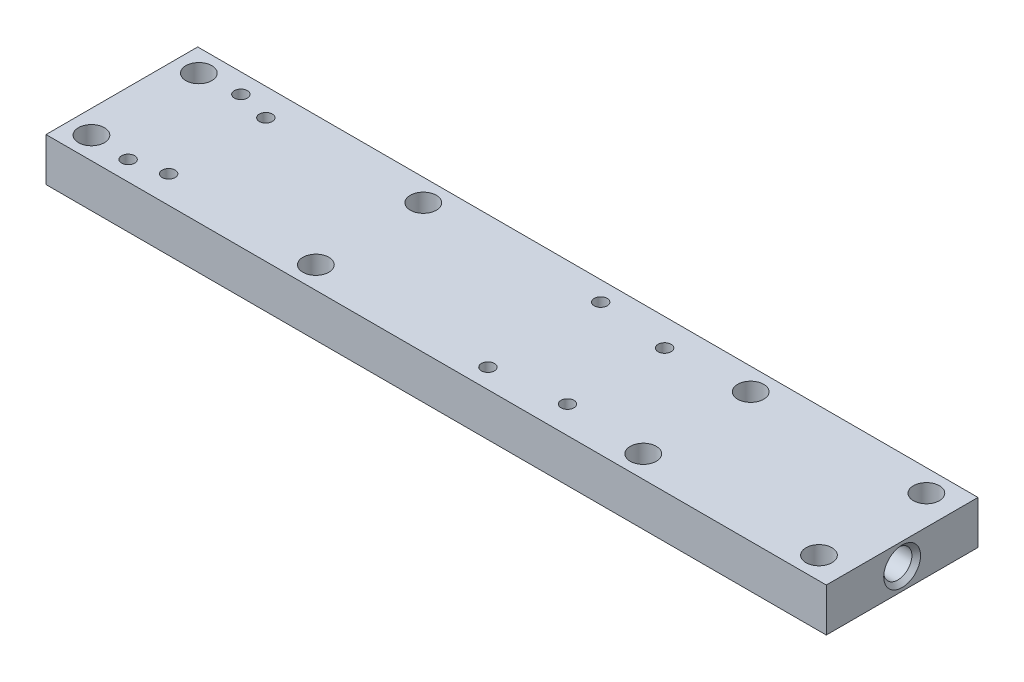
SolidWorks part; units mm, degrees
ref_plane "Front Plane" through (0, 0, 0) normal (0, 0, 1) x (1, 0, 0)
ref_plane "Top Plane" through (0, 0, 0) normal (0, 1, 0) x (1, 0, 0)
ref_plane "Right Plane" through (0, 0, 0) normal (1, 0, 0) x (0, 0, -1)
sketch "Sketch1" plane through (0, 0, 0) normal (0, 1, 0) x (1, 0, 0)
  line L0 (0, -55) -> (0, 55) construction
  line L1 (-90, 17.5) -> (90, 17.5)
  line L2 (-90, 17.5) -> (-90, -17.5)
  line L3 (-90, -17.5) -> (90, -17.5)
  line L4 (90, 17.5) -> (90, -17.5)
  line L5 (-5.5, 0) -> (5.5, 0) construction
  point P4 (0, 17.5)
  point P7 (-90, 0)
  dimension "D1" = 180
  dimension "D2" = 35
extrude "Boss-Extrude1" add sketch "Sketch1" along normal mid plane 10
sketch "Sketch3" plane through (90, 0, 0) normal (1, 0, 0) x (0, 0, -1)
  circle A0 centre (0, 0) radius 3.25
  dimension "D1" = 6.5
extrude "Cut-Extrude1" cut sketch "Sketch3" against normal through all
chamfer "Chamfer1" distance 1 angle 45 1 edges at (90, 0, -3.25)
chamfer "Chamfer2" distance 1 angle 45 1 edges at (-90, 0, -3.25)
sketch "Sketch4" plane through (0, 0, 0) normal (0, 0, 1) x (1, 0, 0)
sketch "Sketch5" plane through (0, 5, 0) normal (0, 1, 0) x (1, 0, 0)
  line L6 (-68, 11.2) -> (-68, -11.2) construction
  line L7 (-5.5, 0) -> (5.5, 0) construction
  line L8 (24, 11.2) -> (24, -11.2) construction
  line L9 (-90, 17.5) -> (-90, -17.5) construction
  circle A0 centre (-68, -11.2) radius 1.5
  circle A1 centre (-68, 11.2) radius 1.5
  circle A2 centre (24, 11.2) radius 1.5
  circle A3 centre (24, -11.2) radius 1.5
  point P4 (-68, 0)
  point P7 (24, 0)
  dimension "D4" = 3
  dimension "D5" = 3
  dimension "D6" = 3
  dimension "D7" = 3
  dimension "D1" = 92
  dimension "D2" = 22.4
  dimension "D3" = 22.4
  dimension "D8" = 22
extrude "Cut-Extrude2" cut sketch "Sketch5" against normal blind 10
sketch "Sketch18" plane through (0, 5, 0) normal (0, 1, 0) x (1, 0, 0)
  line L0 (-75.5526, 13) -> (-75.5526, -13) construction
  line L1 (-75.5526, -13) -> (7.4474, -13) construction
  line L2 (7.4474, -13) -> (7.4474, 13) construction
  line L3 (7.4474, 13) -> (-75.5526, 13) construction
  line L4 (-5.5, 0) -> (5.5, 0) construction
  circle A0 centre (-75.5526, 13) radius 1.5
  circle A1 centre (-75.5526, -13) radius 1.5
  circle A2 centre (7.4474, -13) radius 1.5
  circle A3 centre (7.4474, 13) radius 1.5
  point P2 (-75.5526, 0)
  dimension "D3" = 3
  dimension "D4" = 3
  dimension "D5" = 3
  dimension "D6" = 3
  dimension "D1" = 83
  dimension "D2" = 26
extrude "Cut-Extrude3" cut sketch "Sketch18" against normal blind 36
sketch "Sketch19" plane through (0, 5, 0) normal (0, 1, 0) x (1, 0, 0)
  line L0 (-84.6324, 12.3902) -> (-84.6324, -12.3902) construction
  line L1 (-84.6324, -12.3902) -> (83.204, -12.3902) construction
  line L2 (83.204, -12.3902) -> (83.204, 12.3902) construction
  line L3 (83.204, 12.3902) -> (-84.6324, 12.3902) construction
  line L4 (-5.5, 0) -> (5.5, 0) construction
  circle A0 centre (-84.6324, 12.3902) radius 3
  circle A1 centre (-84.6324, -12.3902) radius 3
  circle A2 centre (83.204, 12.3902) radius 3
  circle A3 centre (83.204, -12.3902) radius 3
  circle A4 centre (42.6762, -12.3902) radius 3
  circle A5 centre (42.6762, 12.3902) radius 3
  circle A6 centre (-32.8527, -12.3902) radius 3
  circle A7 centre (-32.8527, 12.3902) radius 3
  point P14 (-84.6324, 0)
  dimension "D1" = 6
  dimension "D2" = 6
  dimension "D3" = 6
  dimension "D4" = 6
  dimension "D5" = 6
  dimension "D6" = 6
  dimension "D7" = 6
  dimension "D8" = 6
extrude "Cut-Extrude4" cut sketch "Sketch19" against normal blind 10
